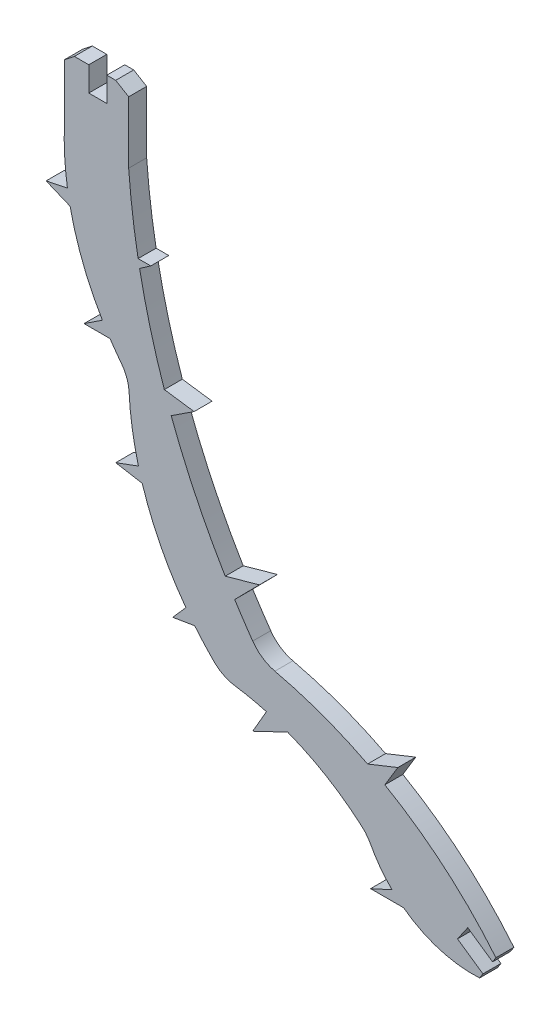
SolidWorks part; units mm, degrees
ref_plane "Front Plane" through (0, 0, 0) normal (0, 0, 1) x (1, 0, 0)
ref_plane "Top Plane" through (0, 0, 0) normal (0, 1, 0) x (1, 0, 0)
ref_plane "Right Plane" through (0, 0, 0) normal (1, 0, 0) x (0, 0, -1)
sketch "Sketch1" plane through (0, 0, 0) normal (0, 0, 1) x (1, 0, 0)
  line L0 (0, -7.483) -> (0, -5.4086)
  line L1 (0, -7.7205) -> (0, -1.8797) construction
  line L2 (0, -7.483) -> (-1.524, -7.483)
  line L3 (-1.524, -7.483) -> (-1.524, -5.4066)
  line L4 (-1.524, -5.4066) -> (-2.748, -5.4066)
  line L5 (0, -5.4086) -> (0.7554, -5.4086)
  line L6 (0.7554, -5.4086) -> (1.853, -6.0665)
  line L7 (1.853, -6.0665) -> (1.853, -11.3027)
  line L8 (-2.748, -5.4066) -> (-3.581, -6.0645)
  line L9 (-3.581, -6.0645) -> (-3.581, -10.7517)
  line L10 (32.9392, -53.6403) -> (32.6585, -54.0838)
  line L11 (32.2506, -54.7282) -> (30.124, -53.2564) construction
  line L12 (32.6585, -54.0838) -> (30.5577, -52.6299)
  line L13 (31.8428, -55.3726) -> (29.6904, -53.883)
  line L14 (31.8428, -55.3726) -> (31.5621, -55.816)
  line L15 (30.5577, -52.6299) -> (29.6904, -53.883)
  line L16 (32.6843, -54.1016) -> (30.5577, -52.6299) construction
  line L17 (31.817, -55.3548) -> (29.6904, -53.883) construction
  line L18 (-3.331, -15.3492) -> (-5.1356, -15.7251)
  line L19 (-5.1356, -15.7251) -> (-3.1069, -16.5687)
  line L20 (-0.3717, -23.5584) -> (-1.9239, -24.5836)
  line L21 (-1.9239, -24.5836) -> (0.2762, -24.5836)
  line L22 (2.6796, -32.7232) -> (0.7554, -33.4421)
  line L23 (0.7554, -33.4421) -> (3.0011, -33.8311)
  line L24 (6.6986, -41.0929) -> (5.5837, -42.3618)
  line L25 (5.5837, -42.3618) -> (7.4434, -42.0512)
  line L26 (13.5141, -45.3171) -> (12.3542, -47.3279)
  line L27 (12.3542, -47.3279) -> (15.3151, -45.9147)
  line L28 (24.1498, -53.051) -> (22.3287, -53.883)
  line L29 (22.3287, -53.883) -> (25.1224, -53.883)
  line L30 (23.54, -45.6654) -> (24.6377, -43.8479)
  line L31 (24.6377, -43.8479) -> (22.0781, -44.8696)
  line L32 (10.8289, -38.433) -> (12.9204, -36.3132)
  line L33 (12.9204, -36.3132) -> (10.0253, -37.1278)
  line L34 (5.4537, -27.6454) -> (7.3918, -26.3755)
  line L35 (7.3918, -26.3755) -> (4.871, -26.0236)
  line L36 (2.7763, -18.192) -> (3.7236, -17.5301)
  line L37 (3.7236, -17.5301) -> (2.6514, -17.5301)
  arc A0 (1.853, -11.3027) -> (2.6514, -17.5301) centre (60.5043, -6.9482) ccw
  arc A1 (14.2308, -41.988) -> (22.0781, -44.8696) centre (6.4301, -75.3573) cw
  arc A2 (31.5621, -55.816) -> (25.1224, -53.883) centre (30.9848, -46.0459) cw
  arc A3 (21.6095, -49.7038) -> (15.3151, -45.9147) centre (7.8216, -65.4858) ccw
  arc A4 (9.0646, -43.8479) -> (7.4434, -42.0512) centre (26.6232, -26.3755) cw
  arc A5 (-3.581, -10.7517) -> (-3.331, -15.3492) centre (19.3516, -11.8104) ccw
  arc A6 (22.3287, -50.6132) -> (21.6095, -49.7038) centre (19.5206, -52.0948) ccw
  arc A7 (12.3542, -40.7195) -> (14.2308, -41.988) centre (14.9535, -38.8964) ccw
  arc A8 (10.8555, -44.75) -> (9.0646, -43.8479) centre (11.3152, -41.6084) cw
  arc A9 (1.8866, -27.6765) -> (1.2232, -25.8953) centre (-1.284, -27.8433) ccw
  arc A10 (-3.1069, -16.5687) -> (-0.3717, -23.5584) centre (19.3516, -11.8104) ccw
  arc A11 (2.7763, -18.192) -> (4.871, -26.0236) centre (60.5043, -6.9482) ccw
  arc A12 (0.2762, -24.5836) -> (1.2232, -25.8953) centre (19.3516, -11.8104) ccw
  arc A13 (5.4537, -27.6454) -> (10.0253, -37.1278) centre (60.5043, -6.9482) ccw
  arc A14 (2.6796, -32.7232) -> (1.8866, -27.6765) centre (26.6232, -26.3755) cw
  arc A15 (10.8289, -38.433) -> (12.3542, -40.7195) centre (60.5043, -6.9482) ccw
  arc A16 (6.6986, -41.0929) -> (3.0011, -33.8311) centre (26.6232, -26.3755) cw
  arc A17 (13.5141, -45.3171) -> (10.8555, -44.75) centre (7.8216, -65.4858) ccw
  arc A18 (23.54, -45.6654) -> (32.9392, -53.6403) centre (6.4301, -75.3573) cw
  arc A19 (24.1498, -53.051) -> (22.3287, -50.6132) centre (30.9848, -46.0459) cw
  dimension "D1" = 3.175
  dimension "D2" = 0.762
  dimension "D3" = 0.762
extrude "Boss-Extrude1" add sketch "Sketch1" along normal blind 1.524
